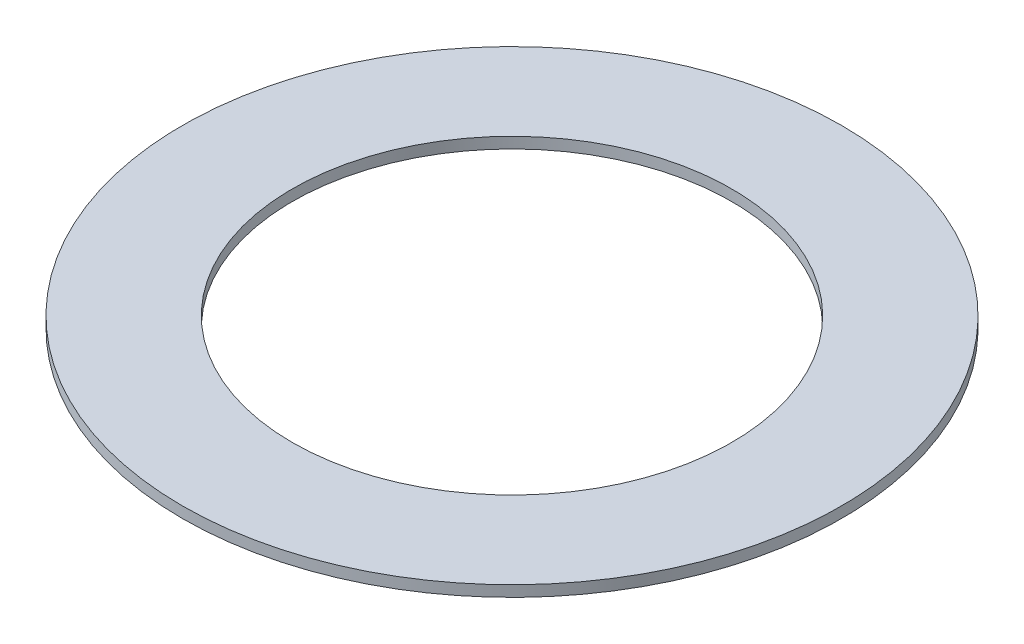
SolidWorks part; units mm, degrees
ref_plane "Front" through (0, 0, 0) normal (0, 0, 1) x (1, 0, 0)
ref_plane "Top" through (0, 0, 0) normal (0, 1, 0) x (1, 0, 0)
ref_plane "Right" through (0, 0, 0) normal (1, 0, 0) x (0, 0, -1)
sketch "Sketch1" plane through (0, 0, 0) normal (1, 0, 0) x (0, 0, -1)
  line L0 (0, 12.3439) -> (0, 0) construction
  line L1 (0, 0) -> (8.5784, 0) construction
  line L3 (4, 0.1) -> (6, 0.1)
  line L4 (4, 0.1) -> (4, -0.1)
  line L5 (4, -0.1) -> (6, -0.1)
  line L6 (6, 0.1) -> (6, -0.1)
  dimension "D1" = 8
  dimension "D2" = 12
  dimension "D3" = 0.2
revolve "Revolve1" add sketch "Sketch1" angle 360 about L0
